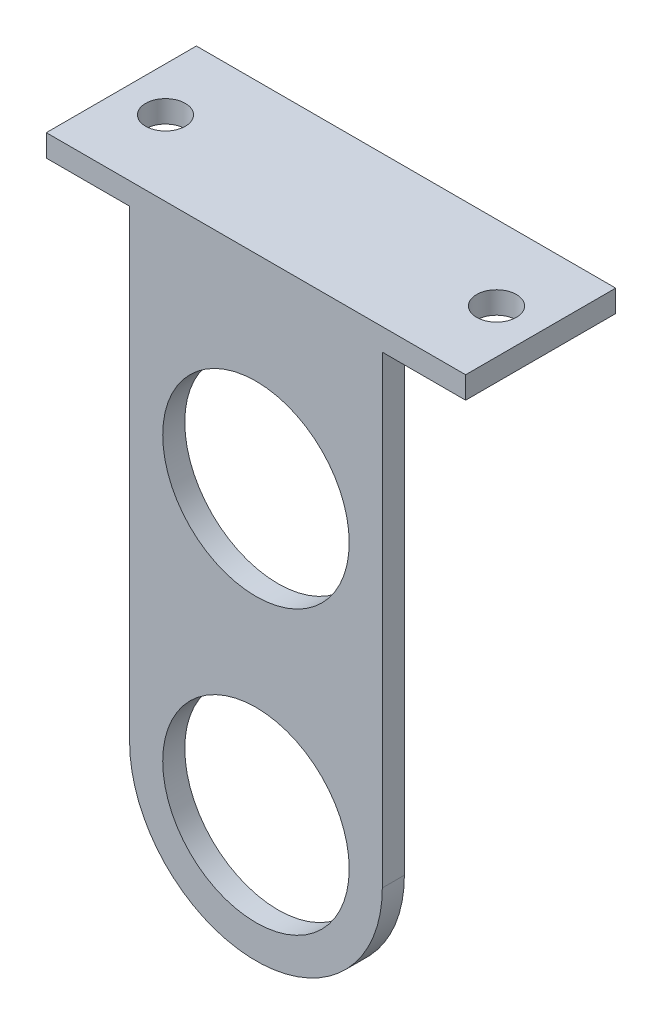
SolidWorks part; units mm, degrees
ref_plane "Front Plane" through (0, 0, 0) normal (0, 0, 1) x (1, 0, 0)
ref_plane "Top Plane" through (0, 0, 0) normal (0, 1, 0) x (1, 0, 0)
ref_plane "Right Plane" through (0, 0, 0) normal (1, 0, 0) x (0, 0, -1)
sketch "Sketch1" plane through (0, 0, 0) normal (0, 0, 1) x (1, 0, 0)
  line L0 (55, 0) -> (-55, 0) construction
  line L1 (0, -12.8) -> (0, 12.8) construction
  line L2 (-11.45, -12.8) -> (-11.45, 29.25)
  line L3 (11.45, -12.8) -> (11.45, 29.25)
  line L5 (-11.45, 29.25) -> (11.45, 29.25)
  circle A0 centre (0, 12.8) radius 7.95 construction
  circle A1 centre (0, -12.8) radius 7.95 construction
  circle A2 centre (0, 12.8) radius 8.45
  circle A3 centre (0, -12.8) radius 8.45
  arc A4 (-11.45, -12.8) -> (11.45, -12.8) centre (0, -12.8) ccw
  arc A5 (11.45, 12.8) -> (-11.45, 12.8) centre (0, 12.8) ccw construction
  point P2 (-11.45, -13.8104)
  point P12 (0, 0)
  point P17 (-13.7834, 29.25)
  point P19 (-10.6341, 29.25)
  point P21 (-11.4235, 13.5791)
  point P22 (11.45, -15.4217)
  point P23 (0, -13.1348)
  dimension "D1" = 15.9
  dimension "D2" = 41.5
  dimension "D4" = 3
  dimension "D5" = 5
  dimension "D3" = 0.5
extrude "Boss-Extrude1" add sketch "Sketch1" along normal mid plane 2
sketch "Sketch4" plane through (0, 29.25, 0) normal (0, 1, 0) x (1, 0, 0)
  line L5 (0, -7.48) -> (0, 7.48) construction
  line L6 (-19, -1) -> (19, -1)
  line L7 (-19, -1) -> (-19, 12.6)
  line L8 (-19, 12.6) -> (19, 12.6)
  line L9 (19, -1) -> (19, 12.6)
  circle A0 centre (-15, 5.8) radius 1.5 construction
  circle A2 centre (15, 5.8) radius 1.5 construction
  circle A3 centre (-15, 5.8) radius 1.8
  circle A4 centre (15, 5.8) radius 1.8
  point P4 (0, 0)
  point P5 (-32.3439, 19.1555)
  point P9 (-27.25, 8.2547)
  point P14 (0, 0)
  point P15 (-19, 5.8)
  point P16 (-32.288, 12.4473)
  point P21 (-31.25, 13.957)
  point P22 (-31.25, 13.169)
  point P23 (32.7789, 13.3164)
  point P24 (0, 12.6)
  point P26 (-31.25, 8.1675)
  point P27 (-31.25, 11.0733)
  dimension "D1" = 30
  dimension "D2" = 2.5
  dimension "D3" = 3
  dimension "D5" = 5
  dimension "D4" = 0.3
extrude "Boss-Extrude2" add sketch "Sketch4" along normal blind 2
sketch "Sketch5" plane through (0, 0, 1) normal (0, 0, 1) x (1, 0, 0)
  line L0 (-19, 29.25) -> (-11.45, 14.25)
  line L1 (-11.45, 29.25) -> (-11.45, -12.8) construction
  point P5 (0, 0)
  dimension "D1" = 15
